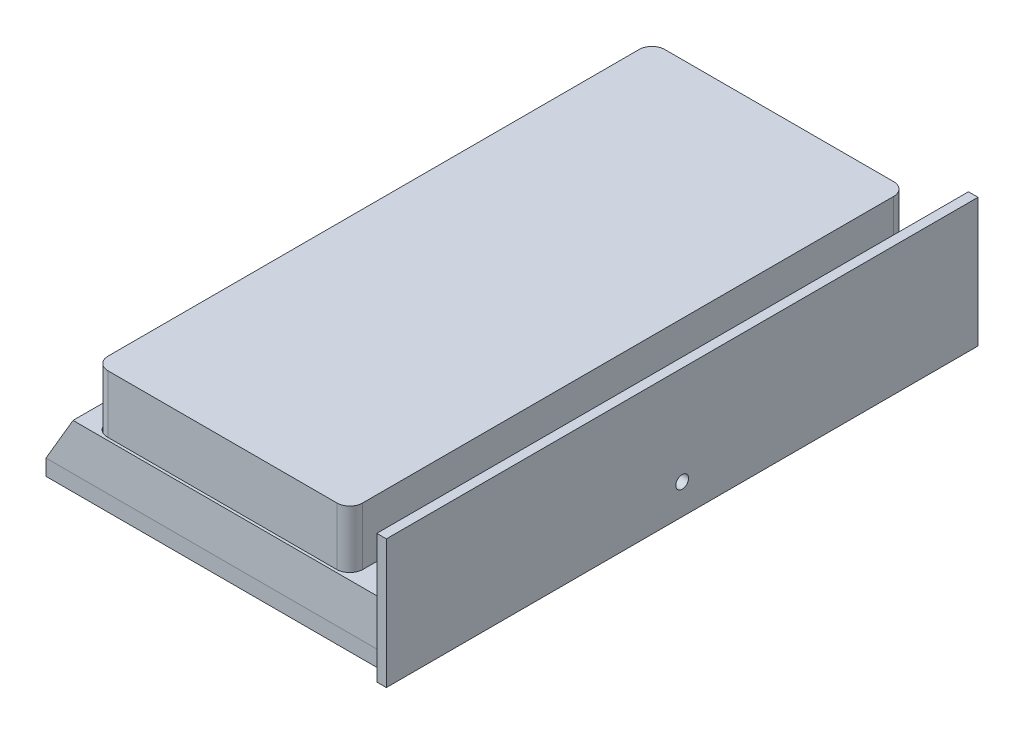
SolidWorks part; units mm, degrees
ref_plane "Front" through (0, 0, 0) normal (0, 0, 1) x (1, 0, 0)
ref_plane "Top" through (0, 0, 0) normal (0, 1, 0) x (1, 0, 0)
ref_plane "Right" through (0, 0, 0) normal (1, 0, 0) x (0, 0, -1)
sketch "Sketch1" plane through (0, 0, 0) normal (0, 1, 0) x (1, 0, 0)
  line L1 (-40, 87.5) -> (40, 87.5)
  line L2 (-40, 87.5) -> (-40, -87.5)
  line L3 (-40, -87.5) -> (40, -87.5)
  line L4 (40, 87.5) -> (40, -87.5)
  line L5 (0, -87.5) -> (0, 87.5) construction
  line L6 (-40, 0) -> (40, 0) construction
  point P0 (0, 0)
  dimension "D1" = 80
  dimension "D2" = 175
extrude "Boss-Extrude1" add sketch "Sketch1" along normal blind 33
fillet "Fillet1" radius 4 4 edges at (-40, 16.5, -87.5) (40, 16.5, -87.5) (-40, 16.5, 87.5) (40, 16.5, 87.5)
sketch "Sketch2" plane through (0, 0, 0) normal (0, 1, 0) x (1, 0, 0)
  line L5 (-54, 89) -> (54, 89)
  line L6 (-54, 89) -> (-54, -89)
  line L7 (-54, -89) -> (54, -89)
  line L8 (36, 87.65) -> (-36, 87.65)
  line L9 (-40.15, 83.5) -> (-40.15, -83.5)
  line L10 (-36, -87.65) -> (36, -87.65)
  line L11 (40.15, -83.5) -> (40.15, 83.5)
  line L12 (36, 87.65) -> (-36, 87.65)
  line L13 (-40.15, 83.5) -> (-40.15, -83.5)
  line L14 (-36, -87.65) -> (36, -87.65)
  line L15 (40.15, -83.5) -> (40.15, 83.5)
  line L16 (54, 89) -> (54, -89)
  line L17 (0, -89) -> (0, 89) construction
  line L18 (-54, 0) -> (54, 0) construction
  arc A8 (-36, 87.65) -> (-40.15, 83.5) centre (-36, 83.5) ccw
  arc A9 (-40.15, -83.5) -> (-36, -87.65) centre (-36, -83.5) ccw
  arc A10 (36, -87.65) -> (40.15, -83.5) centre (36, -83.5) ccw
  arc A11 (40.15, 83.5) -> (36, 87.65) centre (36, 83.5) ccw
  arc A12 (-36, 87.65) -> (-40.15, 83.5) centre (-36, 83.5) ccw
  arc A13 (-40.15, -83.5) -> (-36, -87.65) centre (-36, -83.5) ccw
  arc A14 (36, -87.65) -> (40.15, -83.5) centre (36, -83.5) ccw
  arc A15 (40.15, 83.5) -> (36, 87.65) centre (36, 83.5) ccw
  point P0 (0, 0)
  dimension "D2" = 108
  dimension "D3" = 178
  dimension "D1" = 0.15
extrude "Boss-Extrude2" add sketch "Sketch2" along normal blind 15 separate body
sketch "Sketch3" plane through (0, 0, 0) normal (0, -1, 0) x (1, 0, 0)
  line L4 (54, -89) -> (54, 89)
  line L5 (54, 89) -> (-54, 89)
  line L6 (-54, 89) -> (-54, -89)
  line L7 (-54, -89) -> (54, -89)
  line L8 (54, -89) -> (54, 89)
  line L9 (54, 89) -> (-54, 89)
  line L10 (-54, 89) -> (-54, -89)
  line L11 (-54, -89) -> (54, -89)
  dimension "D1" = 0
extrude "Boss-Extrude3" add sketch "Sketch3" along normal blind 4
chamfer "Chamfer1" distance 14 distance2 0.5 2 edges at (0, 15, -89) (0, 15, 89)
chamfer "Chamfer2" distance 14 distance2 8 1 edges at (-54, 15, 0)
sketch "Sketch8" plane through (54, 0, 0) normal (1, 0, 0) x (0, 0, -1)
  line L0 (89, -4) -> (-89, -4) construction
  line L1 (-93, -4) -> (93, -4)
  line L2 (-93, -4) -> (-93, 36.5)
  line L3 (-93, 36.5) -> (93, 36.5)
  line L4 (93, -4) -> (93, 36.5)
  line L5 (0, 0) -> (0, -4) construction
  dimension "D1" = 186
  dimension "D2" = 40.5
extrude "Boss-Extrude4" add sketch "Sketch8" along normal blind 3
sketch "Sketch9" plane through (57, 0, 0) normal (1, 0, 0) x (0, 0, -1)
  line L0 (0, 15) -> (0, -4) construction
  line L1 (-88.5, 15) -> (88.5, 15) construction
  line L2 (-93, -4) -> (93, -4) construction
  circle A0 centre (0, 5.5) radius 2
  dimension "D1" = 4
extrude "Cut-Extrude1" cut sketch "Sketch9" against normal blind 6
chamfer "Chamfer4" distance 17 distance2 4 1 edges at (54, 15, 0)
